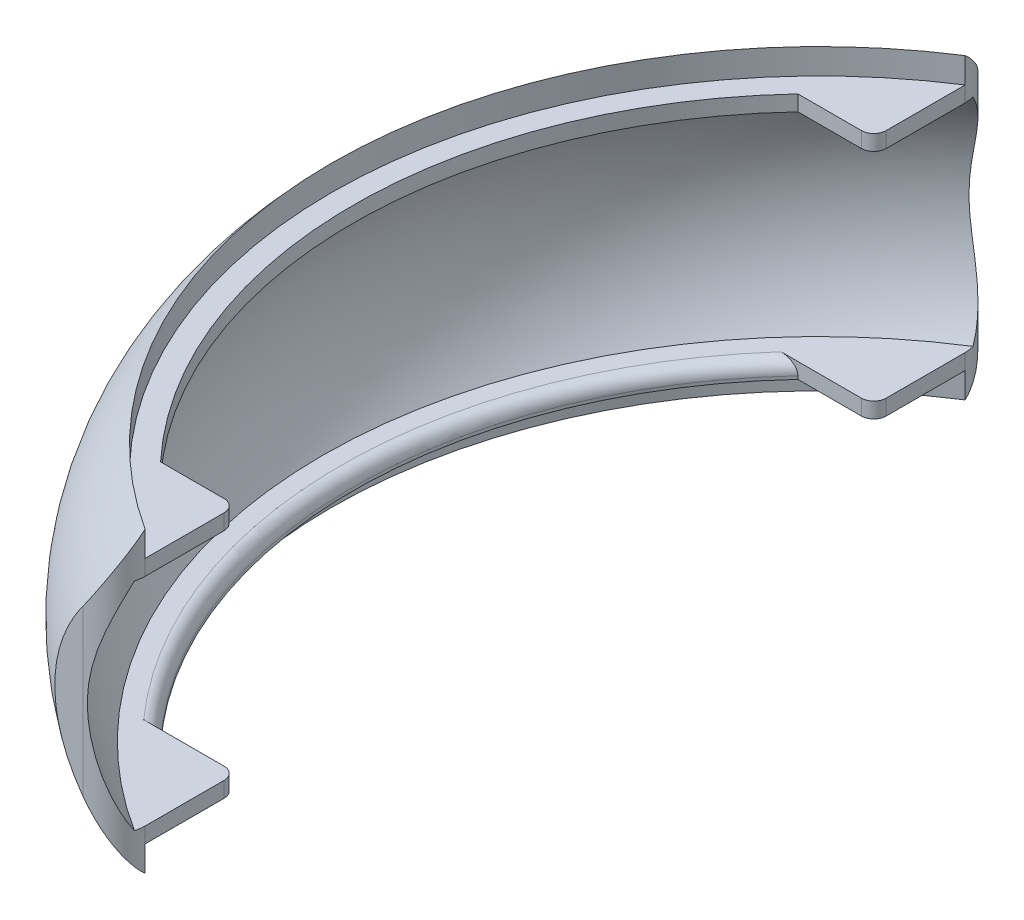
SolidWorks part; units mm, degrees
material "ABS"
ref_plane "Front Plane" through (0, 0, 0) normal (0, 0, 1) x (1, 0, 0)
ref_plane "Top Plane" through (0, 0, 0) normal (0, 1, 0) x (1, 0, 0)
ref_plane "Right Plane" through (0, 0, 0) normal (1, 0, 0) x (0, 0, -1)
sketch "Sketch2" plane through (0, 0, 0) normal (0, 0, 1) x (1, 0, 0)
  line L0 (0, 0) -> (-78.5, 0) construction
  line L1 (0, 0) -> (0, 12.6392) construction
  line L13 (-78.5, 0.9077) -> (-78.5, 30.811) construction
  line L14 (-78.5, -24) -> (-78.5, -19.9)
  line L15 (-78.5, -19.9) -> (-75, -19.9)
  line L16 (-75, -19.9) -> (-75, -17.4)
  line L17 (-75, -17.4) -> (-79.8804, -17.4)
  line L18 (-78.5, 24) -> (-78.5, 19.9)
  line L19 (-78.5, 19.9) -> (-75, 19.9)
  line L20 (-75, 19.9) -> (-75, 17.4)
  line L21 (-75, 17.4) -> (-79.8804, 17.4)
  arc A2 (-78.5, 24) -> (-78.5, -24) centre (-53.0245, 0) ccw
  arc A3 (-79.8804, 17.4) -> (-79.8804, -17.4) centre (-53.0245, 0) ccw
  point P2 (-88.0245, 0)
  dimension "D17" = 3
  dimension "D18" = 35
  dimension "D2" = 78.5
  dimension "D3" = 39.8
  dimension "D10" = 48
  dimension "D11" = 4.1
  dimension "D12" = 2.5
  dimension "D13" = 4.1
  dimension "D14" = 2.5
  dimension "D15" = 3.5
  dimension "D16" = 3.5
sketch "Sketch3" plane through (0, 0, 0) normal (0, 1, 0) x (1, 0, 0)
  line L0 (-42.5, -66) -> (-42.5, 66)
  line L1 (-42.5, 0) -> (-42.5, 75) construction
  line L2 (-42.5, 0) -> (-42.5, -75) construction
  line L3 (0, 0) -> (-78.5, 0) construction
  line L4 (-47.5, -71) -> (-70.0728, -71)
  line L5 (-70.0728, -87.3523) -> (-35.0728, -87.3523)
  line L6 (-35.0728, -87.3523) -> (-35.0728, 87.3523)
  line L7 (0, 0) -> (-93.6111, 0) construction
  line L8 (-70.0728, 87.3523) -> (-35.0728, 87.3523)
  line L9 (-70.0728, -71) -> (-70.0728, -87.3523)
  line L10 (-47.5, 71) -> (-70.0728, 71)
  line L11 (-70.0728, 71) -> (-70.0728, 87.3523)
  arc A0 (-42.5, -66) -> (-47.5, -71) centre (-47.5, -66) cw
  arc A1 (-42.5, 66) -> (-47.5, 71) centre (-47.5, 66) ccw
  point P4 (0, 0)
  point P7 (-42.5, 0)
  point P8 (-42.5, -74.09)
  point P12 (0, 0)
  point P19 (-35.0728, 0)
  point P20 (-42.5, -84.52)
  point P24 (0, 0)
  point P27 (0, 0)
  dimension "D3" = 74.09
  dimension "D6" = 5
  dimension "D1" = 132
  dimension "D2" = 36
  dimension "D4" = 10.43
  dimension "D5" = 35
  dimension "D7" = 75
  dimension "D8" = 75
revolve "Revolve1" add sketch "Sketch2" about L1
extrude "Cut-Extrude1" cut sketch "Sketch3" against normal through all both and the other way through all
sketch "Sketch4" plane through (0, 17.4, 0) normal (0, -1, 0) x (1, 0, 0)
  line L0 (-54.7149, 51.296) -> (-44.4692, 51.296)
  line L1 (-42.5, 61.796) -> (-42.5, 53.2958)
  line L2 (0, 0) -> (-88.0245, 0) construction
  arc A0 (-42.5, 61.796) -> (-42.5, -61.796) centre (0, 0) ccw construction
  arc A1 (-42.5, 61.796) -> (-54.7149, 51.296) centre (0, 0) ccw
  arc A2 (-52.0319, 71) -> (-52.0319, -71) centre (0, 0) ccw construction
  arc A3 (-42.5, 53.2958) -> (-44.4692, 51.296) centre (-44.5, 53.2958) cw
  point P8 (-57.1901, -11.1013)
  point P9 (3.4537, -3.677)
  point P13 (0, 0)
  point P15 (0, 0)
  point P16 (-71.5387, 0)
  point P17 (-80.5514, 0)
  point P18 (-88.0245, 0)
  point P22 (0, 0)
  point P23 (-48.0323, 44.6444)
  point P24 (-46.8181, 50.9667)
  point P25 (-44.7548, 53.272)
  point P26 (-44.9183, 53.4469)
  point P27 (0, 0)
  point P28 (-43.1509, 52.796)
  point P29 (-42.5, 52.5442)
  point P30 (-43.7482, 51.296)
  point P31 (0, 0)
  point P32 (-44.4692, 53.2617)
  dimension "D1" = 10.5
  dimension "D2" = 12.2149
  dimension "D3" = 2
extrude "Boss-Extrude2" add sketch "Sketch4" against normal blind 2.5
mirror "Mirror1" about plane through (0, 0, 0) normal (0, 0, 1) of "Boss-Extrude2"
mirror "Mirror2" about plane through (0, 0, 0) normal (0, 1, 0) of "Mirror1", "Boss-Extrude2"
fillet "Fillet2" radius 2 1 edges at (-75, -17.4, 0)
